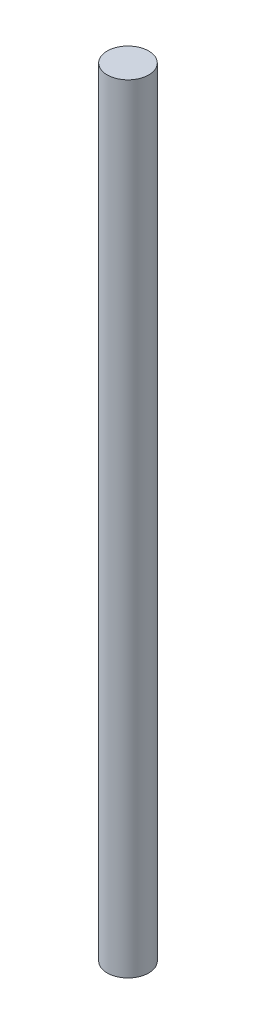
SolidWorks part; units mm, degrees
ref_plane "Спереди" through (0, 0, 0) normal (0, 0, 1) x (1, 0, 0)
ref_plane "Сверху" through (0, 0, 0) normal (0, 1, 0) x (1, 0, 0)
ref_plane "Справа" through (0, 0, 0) normal (1, 0, 0) x (0, 0, -1)
sketch "Эскиз1" plane through (0, 0, 0) normal (0, 1, 0) x (1, 0, 0)
  circle A0 centre (0, 0) radius 8
  dimension "D1" = 16
extrude "Бобышка-Вытянуть1" add sketch "Эскиз1" along normal blind 300
